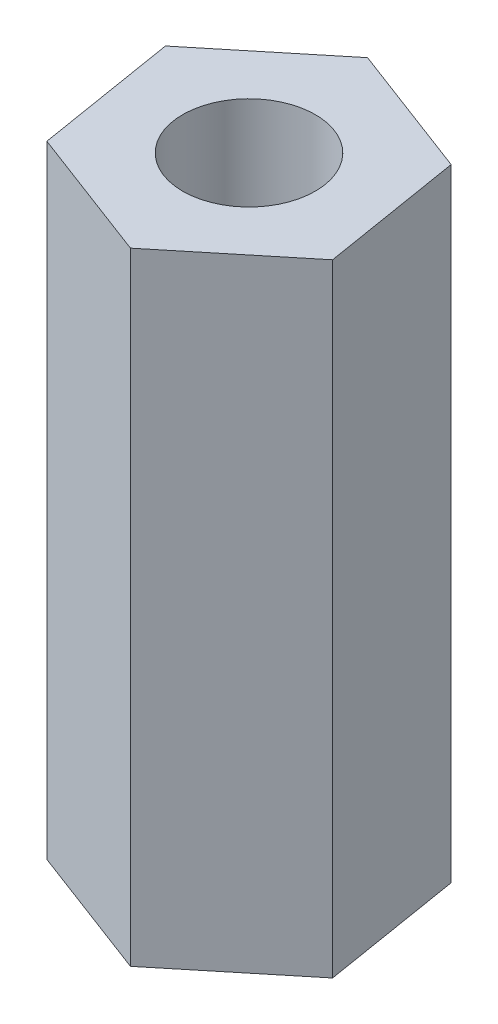
SolidWorks part; units mm, degrees
ref_plane "Front Plane" through (0, 0, 0) normal (0, 0, 1) x (1, 0, 0)
ref_plane "Top Plane" through (0, 0, 0) normal (0, 1, 0) x (1, 0, 0)
ref_plane "Right Plane" through (0, 0, 0) normal (1, 0, 0) x (0, 0, -1)
sketch "Sketch1" plane through (0, 0, 0) normal (0, 1, 0) x (1, 0, 0)
  line L1 (0.5594, -3.4186) -> (3.2403, -1.2249)
  line L2 (3.2403, -1.2249) -> (2.6809, 2.1938)
  line L3 (2.6809, 2.1938) -> (-0.5594, 3.4186)
  line L4 (-0.5594, 3.4186) -> (-3.2403, 1.2249)
  line L5 (-3.2403, 1.2249) -> (-2.6809, -2.1938)
  line L6 (-2.6809, -2.1938) -> (0.5594, -3.4186)
  circle A0 centre (0, 0) radius 1.6
  circle A1 centre (0, 0) radius 3 construction
  dimension "D1" = 3.2
  dimension "D2" = 6
extrude "Boss-Extrude1" add sketch "Sketch1" along normal blind 15
